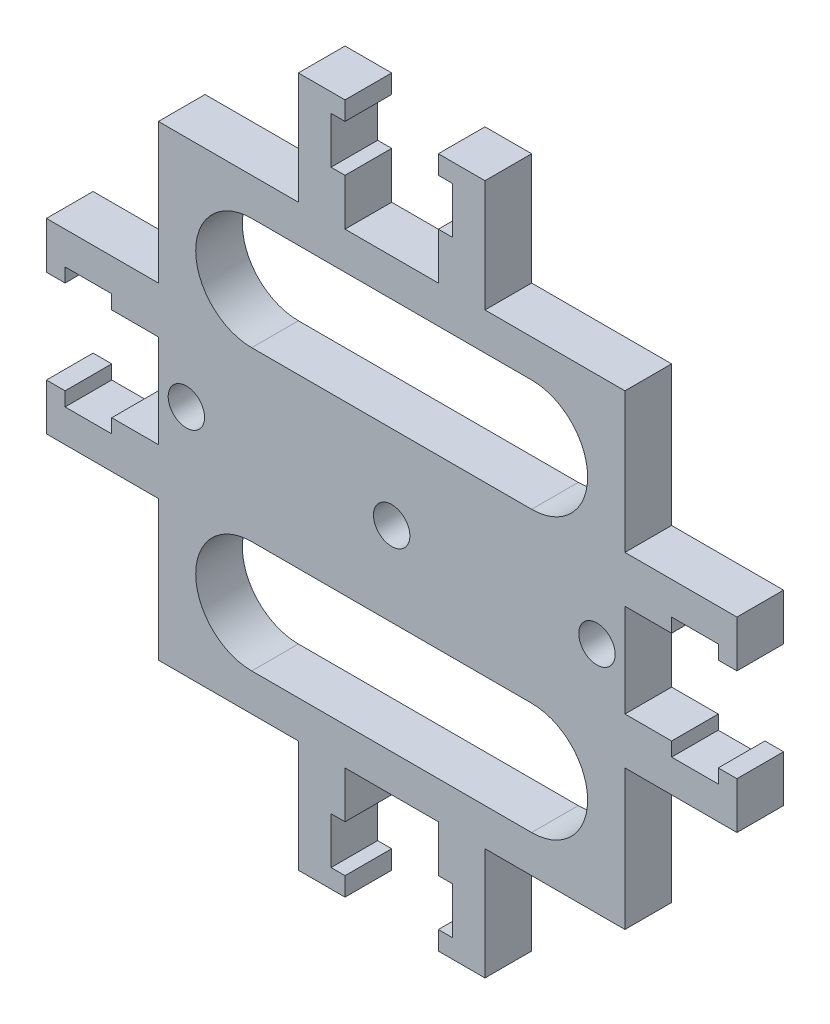
SolidWorks part; units mm, degrees
ref_plane "Plan de face" through (0, 0, 0) normal (0, 0, 1) x (1, 0, 0)
ref_plane "Plan de dessus" through (0, 0, 0) normal (0, 1, 0) x (1, 0, 0)
ref_plane "Plan de droite" through (0, 0, 0) normal (1, 0, 0) x (0, 0, -1)
sketch "Esquisse1" plane through (0, 0, 0) normal (0, 0, 1) x (1, 0, 0)
  line L0 (0, -10.9037) -> (0, 0) construction
  line L1 (0, 0) -> (78.1485, 0) construction
  line L2 (-25, 25) -> (-10, 25)
  line L3 (0, 0) -> (90.4553, 90.4553) construction
  line L4 (10, 25) -> (25, 25)
  line L5 (-25, -25) -> (-10, -25)
  line L6 (25, -25) -> (25, -10)
  line L8 (25, 10) -> (25, 25)
  line L9 (-25, -25) -> (-25, -10)
  line L10 (-25, 10) -> (-25, 25)
  line L11 (-15, 15) -> (15, 15) construction
  line L12 (-15, 21) -> (15, 21)
  line L13 (10, -25) -> (25, -25)
  line L14 (-15, 9) -> (15, 9)
  line L15 (-15, -15) -> (15, -15) construction
  line L16 (-15, -21) -> (15, -21)
  line L17 (-15, -9) -> (15, -9)
  circle A0 centre (0, 0) radius 1.95
  circle A1 centre (22, 0) radius 1.95
  circle A2 centre (-22, 0) radius 1.95
  arc A3 (-15, 21) -> (-15, 9) centre (-15, 15) ccw
  arc A4 (15, 9) -> (15, 21) centre (15, 15) ccw
  arc A5 (-15, -21) -> (-15, -9) centre (-15, -15) cw
  arc A6 (15, -9) -> (15, -21) centre (15, -15) cw
  point P20 (0, 15)
  point P27 (0, 15.2859)
  point P32 (0, -15)
  line B0 (0, -25) -> (0, -13.135) construction
  line B1 (0, -25) -> (-5, -25)
  line B2 (-5, -30) -> (-10, -30) construction
  line B3 (-10, -30) -> (-10, -25)
  line B4 (-5, -30) -> (-5, -25)
  line B5 (0, -25) -> (5, -25)
  line B6 (5, -25) -> (5, -30)
  line B7 (5, -30) -> (10, -30) construction
  line B8 (10, -30) -> (10, -25)
  line B9 (-10, -30) -> (-10, -37)
  line B10 (-10, -37) -> (-5, -37)
  line B11 (-5, -37) -> (-5, -35)
  line B12 (-5, -35) -> (-6.5, -35)
  line B13 (-6.5, -35) -> (-6.5, -30)
  line B14 (-6.5, -30) -> (-5, -30)
  line B15 (5, -35) -> (6.5, -35)
  line B16 (10, -37) -> (5, -37)
  line B17 (5, -37) -> (5, -35)
  line B18 (6.5, -35) -> (6.5, -30)
  line B19 (10, -30) -> (10, -37)
  line B20 (10, -30) -> (10, -25)
  line B21 (5, -30) -> (6.5, -30)
  line B22 (0, -25) -> (0, -13.135) construction
  line B23 (0, -25) -> (5, -25)
  line B24 (5, -30) -> (10, -30) construction
  line B25 (10, -30) -> (10, -25)
  line B26 (5, -30) -> (5, -25)
  line B27 (0, -25) -> (-5, -25)
  line B28 (-5, -25) -> (-5, -30)
  line B29 (-5, -30) -> (-10, -30) construction
  line B30 (-10, -30) -> (-10, -25)
  line B31 (10, -30) -> (10, -37)
  line B32 (10, -37) -> (5, -37)
  line B33 (5, -37) -> (5, -35)
  line B34 (5, -35) -> (6.5, -35)
  line B35 (6.5, -35) -> (6.5, -30)
  line B36 (6.5, -30) -> (5, -30)
  line B37 (-5, -35) -> (-6.5, -35)
  line B38 (-10, -37) -> (-5, -37)
  line B39 (-5, -37) -> (-5, -35)
  line B40 (-6.5, -35) -> (-6.5, -30)
  line B41 (-10, -30) -> (-10, -37)
  line B42 (-10, -30) -> (-10, -25)
  line B43 (-5, -30) -> (-6.5, -30)
  line B44 (0, 25) -> (0, 13.135) construction
  line B45 (0, 25) -> (-5, 25)
  line B46 (-5, 30) -> (-10, 30) construction
  line B47 (-10, 30) -> (-10, 25)
  line B48 (-5, 30) -> (-5, 25)
  line B49 (0, 25) -> (5, 25)
  line B50 (5, 25) -> (5, 30)
  line B51 (5, 30) -> (10, 30) construction
  line B52 (10, 30) -> (10, 25)
  line B53 (-10, 30) -> (-10, 37)
  line B54 (-10, 37) -> (-5, 37)
  line B55 (-5, 37) -> (-5, 35)
  line B56 (-5, 35) -> (-6.5, 35)
  line B57 (-6.5, 35) -> (-6.5, 30)
  line B58 (-6.5, 30) -> (-5, 30)
  line B59 (5, 35) -> (6.5, 35)
  line B60 (10, 37) -> (5, 37)
  line B61 (5, 37) -> (5, 35)
  line B62 (6.5, 35) -> (6.5, 30)
  line B63 (10, 30) -> (10, 37)
  line B64 (10, 30) -> (10, 25)
  line B65 (5, 30) -> (6.5, 30)
  line B66 (25, 0) -> (13.135, 0) construction
  line B67 (25, 0) -> (25, -5)
  line B68 (30, -5) -> (30, -10) construction
  line B69 (30, -10) -> (25, -10)
  line B70 (30, -5) -> (25, -5)
  line B71 (25, 0) -> (25, 5)
  line B72 (25, 5) -> (30, 5)
  line B73 (30, 5) -> (30, 10) construction
  line B74 (30, 10) -> (25, 10)
  line B75 (30, -10) -> (37, -10)
  line B76 (37, -10) -> (37, -5)
  line B77 (37, -5) -> (35, -5)
  line B78 (35, -5) -> (35, -6.5)
  line B79 (35, -6.5) -> (30, -6.5)
  line B80 (30, -6.5) -> (30, -5)
  line B81 (35, 5) -> (35, 6.5)
  line B82 (37, 10) -> (37, 5)
  line B83 (37, 5) -> (35, 5)
  line B84 (35, 6.5) -> (30, 6.5)
  line B85 (30, 10) -> (37, 10)
  line B86 (30, 10) -> (25, 10)
  line B87 (30, 5) -> (30, 6.5)
  line B88 (-25, 0) -> (-13.135, 0) construction
  line B89 (-25, 0) -> (-25, -5)
  line B90 (-30, -5) -> (-30, -10) construction
  line B91 (-30, -10) -> (-25, -10)
  line B92 (-30, -5) -> (-25, -5)
  line B93 (-25, 0) -> (-25, 5)
  line B94 (-25, 5) -> (-30, 5)
  line B95 (-30, 5) -> (-30, 10) construction
  line B96 (-30, 10) -> (-25, 10)
  line B97 (-30, -10) -> (-37, -10)
  line B98 (-37, -10) -> (-37, -5)
  line B99 (-37, -5) -> (-35, -5)
  line B100 (-35, -5) -> (-35, -6.5)
  line B101 (-35, -6.5) -> (-30, -6.5)
  line B102 (-30, -6.5) -> (-30, -5)
  line B103 (-35, 5) -> (-35, 6.5)
  line B104 (-37, 10) -> (-37, 5)
  line B105 (-37, 5) -> (-35, 5)
  line B106 (-35, 6.5) -> (-30, 6.5)
  line B107 (-30, 10) -> (-37, 10)
  line B108 (-30, 10) -> (-25, 10)
  line B109 (-30, 5) -> (-30, 6.5)
  dimension "D11" = 3.9
  dimension "D4" = 3.9
  dimension "D8" = 6
  dimension "D2" = 50
  dimension "D3" = 50
  dimension "D5" = 45
  dimension "D6" = 22
  dimension "D7" = 10
sketch_block_instance "Insert plots ep 5mm avec ergots-1"
sketch_block "Insert plots ep 5mm avec ergots" parameters "D1"=10, "D2"=5, "D3"=5, "D4"=5, "D5"=2, "D6"=1.5, "D7"=2, "D8"=2, "D9"=2.0716, "D10"=2
sketch_block_instance "Insert plots ep 5mm avec ergots-3"
sketch_block_instance "Insert plots ep 5mm avec ergots-4"
sketch_block_instance "Insert plots ep 5mm avec ergots-6"
sketch_block_instance "Insert plots ep 5mm avec ergots-7"
extrude "Boss.-Extru.1" add sketch "Esquisse1" along normal blind 5
